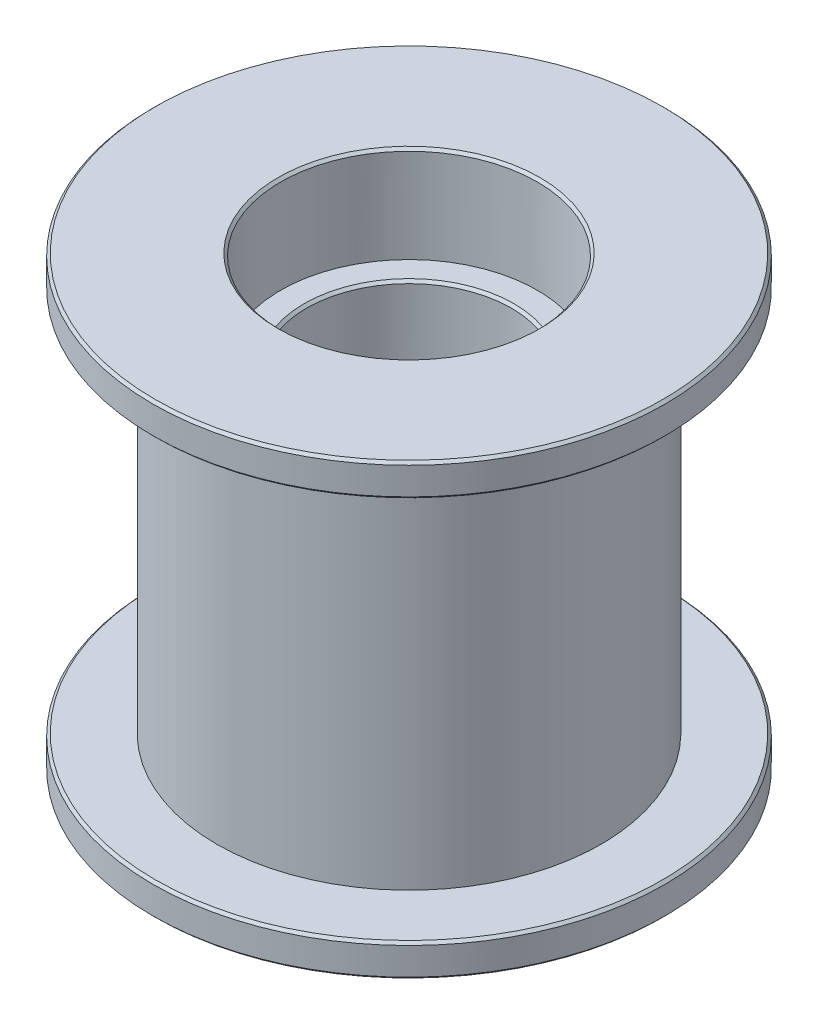
SolidWorks part; units mm, degrees
material "6061-T6 (SS)"
ref_plane "Front Plane" through (0, 0, 0) normal (0, 0, 1) x (1, 0, 0)
ref_plane "Top Plane" through (0, 0, 0) normal (0, 1, 0) x (1, 0, 0)
ref_plane "Right Plane" through (0, 0, 0) normal (1, 0, 0) x (0, 0, -1)
sketch "Sketch1" plane through (0, 0, 0) normal (0, 0, 1) x (1, 0, 0)
  line L0 (6.3627, 0) -> (12.7, 0)
  line L1 (12.7, 0) -> (12.7, 1.6125)
  line L2 (12.7, 1.6125) -> (9.525, 1.6125)
  line L3 (9.525, 1.6125) -> (9.525, 20.6125)
  line L4 (9.525, 20.6125) -> (12.7, 20.6125)
  line L5 (12.7, 20.6125) -> (12.7, 22.225)
  line L6 (12.7, 22.225) -> (6.3627, 22.225)
  line L7 (0, 22.225) -> (0, 0) construction
  line L8 (6.3627, 0) -> (6.3627, 4.7752)
  line L9 (6.3627, 4.7752) -> (5.08, 4.7752)
  line L10 (5.08, 4.7752) -> (5.08, 17.4498)
  line L11 (5.08, 17.4498) -> (6.3627, 17.4498)
  line L12 (6.3627, 17.4498) -> (6.3627, 22.225)
  line L13 (6.3627, 22.225) -> (0, 22.225) construction
  line L14 (0, 0) -> (6.3627, 0) construction
  dimension "D3" = 19
  dimension "D4" = 22.225
  dimension "D1" = 19.05
  dimension "D2" = 25.4
  dimension "D5" = 12.7254
  dimension "D6" = 4.7752
  dimension "D7" = 10.16
revolve "Revolve1" add sketch "Sketch1" angle 360 about L7
chamfer "Chamfer1" distance 0.127 angle 45 8 edges at (0, 20.6125, 12.7) (0, 1.6125, 12.7) (0, 0, 6.3627) (0, 0, 12.7) (0, 17.4498, 5.08) (0, 4.7752, 5.08) (0, 22.225, 12.7) (0, 22.225, 6.3627)
equation "\"D3@Sketch1\"=19mm"
